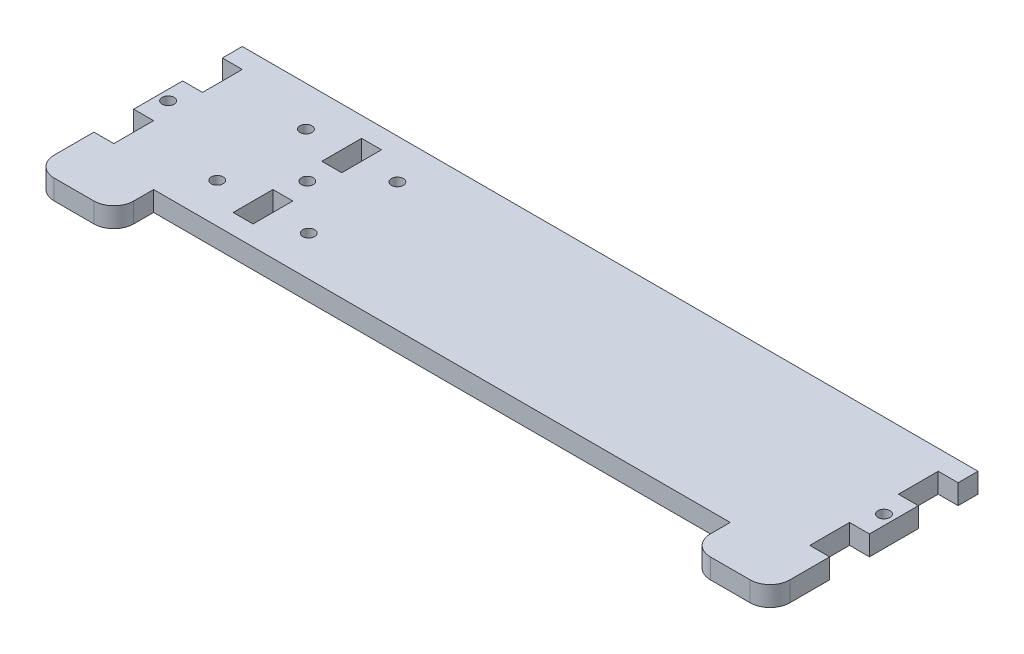
SolidWorks part; units mm, degrees
ref_plane "前视基准面" through (0, 0, 0) normal (0, 0, 1) x (1, 0, 0)
ref_plane "上视基准面" through (0, 0, 0) normal (0, 1, 0) x (1, 0, 0)
ref_plane "右视基准面" through (0, 0, 0) normal (1, 0, 0) x (0, 0, -1)
sketch "草图1" plane through (0, 0, 0) normal (0, 1, 0) x (1, 0, 0)
  line L0 (0, 0) -> (0, -5)
  line L1 (20, 0) -> (165, 0)
  line L2 (0, 0) -> (0, 5)
  line L3 (0, 42.3) -> (185, 42.3)
  line L4 (185, 0) -> (185, 5)
  line L5 (5, -10) -> (15, -10)
  line L6 (20, -5) -> (20, 0)
  line L7 (185, 0) -> (185, -5)
  line L8 (180, -10) -> (170, -10)
  line L9 (165, -5) -> (165, 0)
  line L10 (5, 48.5782) -> (5, -33.983) construction
  line L11 (35, 48.5782) -> (35, -21.9468) construction
  line L12 (40, 48.5782) -> (40, -23.2632) construction
  line L13 (180, 53.0918) -> (180, -27.4007) construction
  line L14 (0, 37.3) -> (0, 42.3)
  line L15 (0, 37.3) -> (5, 37.3)
  line L16 (0, 15) -> (0, 27.3)
  line L17 (0, 27.3) -> (5, 27.3)
  line L18 (5, 37.3) -> (5, 27.3)
  line L19 (0, 15) -> (5, 15)
  line L20 (185, 37.3) -> (185, 42.3)
  line L21 (0, 5) -> (5, 5)
  line L22 (5, 15) -> (5, 5)
  line L23 (35, 37.3) -> (40, 37.3)
  line L24 (35, 37.3) -> (35, 27.3)
  line L25 (35, 27.3) -> (40, 27.3)
  line L26 (40, 37.3) -> (40, 27.3)
  line L27 (35, 15) -> (40, 15)
  line L28 (35, 15) -> (35, 5)
  line L29 (35, 5) -> (40, 5)
  line L30 (40, 15) -> (40, 5)
  line L31 (180, 37.3) -> (185, 37.3)
  line L32 (180, 37.3) -> (180, 27.3)
  line L33 (180, 27.3) -> (185, 27.3)
  line L34 (185, 15) -> (185, 27.3)
  line L35 (180, 15) -> (185, 15)
  line L36 (180, 15) -> (180, 5)
  line L37 (180, 5) -> (185, 5)
  line L38 (11.2274, 32.3) -> (65.9182, 32.3) construction
  line L39 (24.825, 10) -> (65.9182, 10) construction
  line L40 (26, 39.4529) -> (26, 3.2023) construction
  line L41 (49, 37.3) -> (49, 3.2023) construction
  circle A0 centre (26, 32.3) radius 1.5
  circle A1 centre (49, 32.3) radius 1.5
  circle A2 centre (26, 10) radius 1.5
  circle A3 centre (49, 10) radius 1.5
  arc A4 (185, -5) -> (180, -10) centre (180, -5) cw
  arc A5 (170, -10) -> (165, -5) centre (170, -5) cw
  arc A6 (0, -5) -> (5, -10) centre (5, -5) ccw
  arc A7 (15, -10) -> (20, -5) centre (15, -5) ccw
  circle A8 centre (2.5, 21.15) radius 1.5
  circle A9 centre (182.5, 21.15) radius 1.5
  circle A10 centre (37.5, 21.15) radius 1.5
  point P52 (37.5, 37.3)
  point P62 (185, -10)
  point P65 (165, -10)
  point P68 (0, -10)
  point P71 (20, -10)
  point P80 (35, 19.4336)
  dimension "D28" = 5
  dimension "D29" = 6.15
  dimension "D31" = 2.5
  dimension "D32" = 6.15
  dimension "D1" = 42.3
  dimension "D2" = 185
  dimension "D3" = 10
  dimension "D4" = 10
  dimension "D5" = 10
  dimension "D6" = 20
  dimension "D7" = 20
  dimension "D8" = 5
  dimension "D9" = 30
  dimension "D10" = 5
  dimension "D11" = 5
  dimension "D12" = 10
  dimension "D13" = 10
  dimension "D14" = 10
  dimension "D15" = 10
  dimension "D16" = 10
  dimension "D17" = 10
  dimension "D18" = 5
  dimension "D19" = 5
  dimension "D20" = 5
  dimension "D21" = 5
  dimension "D22" = 5
  dimension "D23" = 5
  dimension "D24" = 9
  dimension "D25" = 9
  dimension "D26" = 5
  dimension "D27" = 5
  dimension "D30" = 2.5
  dimension "D33" = 2.5
extrude "凸台-拉伸1" add sketch "草图1" along normal blind 5
